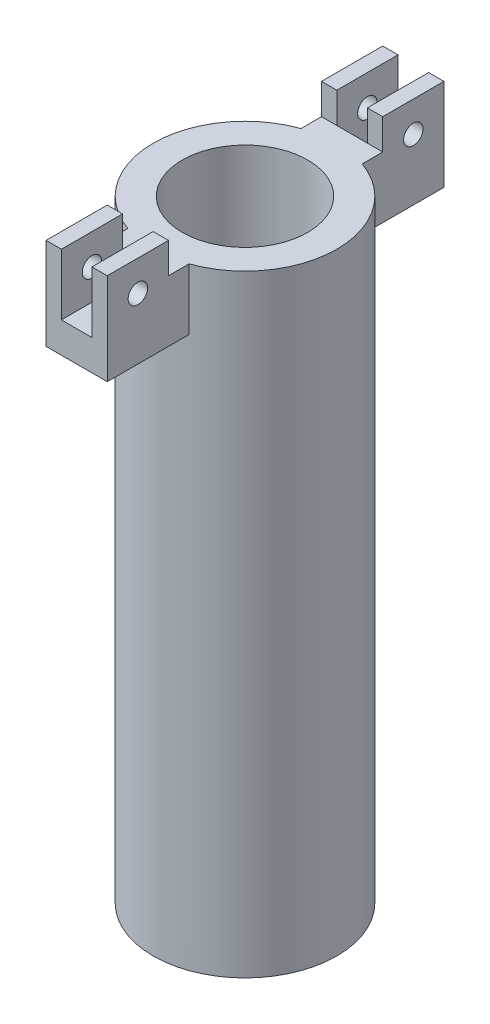
SolidWorks part; units mm, degrees
ref_plane "Front Plane" through (0, 0, 0) normal (0, 0, 1) x (1, 0, 0)
ref_plane "Top Plane" through (0, 0, 0) normal (0, 1, 0) x (1, 0, 0)
ref_plane "Right Plane" through (0, 0, 0) normal (1, 0, 0) x (0, 0, -1)
sketch "Sketch1" plane through (0, 0, 0) normal (0, 1, 0) x (1, 0, 0)
  circle A0 centre (0, 0) radius 30
  dimension "D1" = 60
extrude "Boss-Extrude1" add sketch "Sketch1" along normal mid plane 200
sketch "Sketch2" plane through (0, 100, 0) normal (0, 1, 0) x (1, 0, 0)
  circle A0 centre (0, 0) radius 20.5
  dimension "D1" = 41
extrude "Cut-Extrude1" cut sketch "Sketch2" against normal blind 150
sketch "Sketch3" plane through (0, 0, 0) normal (1, 0, 0) x (0, 0, -1)
  line L0 (20.5, 104.0939) -> (20.5, -49895.9061) construction
  line L1 (20.5, 100) -> (35, 100)
  line L2 (35, 100) -> (35, 110)
  line L3 (35, 110) -> (55, 110)
  line L4 (55, 110) -> (55, 80)
  line L5 (55, 80) -> (20.5, 80)
  line L6 (20.5, 100) -> (20.5, 80)
  line L8 (0, -1000) -> (0, 49000) construction
  line L9 (30, 100) -> (-30, 100) construction
  circle A0 centre (45, 100) radius 3.175
  dimension "D4" = 6.35
  dimension "D1" = 20
  dimension "D3" = 20
  dimension "D5" = 10
  dimension "D6" = 10
  dimension "D8" = 45
extrude "Boss-Extrude3" add sketch "Sketch3" along normal mid plane 20
sketch "Sketch4" plane through (0, 0, -55) normal (0, 0, -1) x (-1, 0, 0)
  line L0 (-10, 110) -> (10, 110) construction
  line L1 (-5, 110) -> (5, 110)
  line L2 (-5, 110) -> (-5, 90)
  line L3 (-5, 90) -> (5, 90)
  line L4 (5, 110) -> (5, 90)
  line L5 (0, 110) -> (0, 80) construction
  line L6 (-10, 80) -> (10, 80) construction
  point P10 (0, 0)
  dimension "D1" = 10
  dimension "D2" = 20
extrude "Cut-Extrude2" cut sketch "Sketch4" against normal up to surface (20 mm away) up to face at (0, 105, -35)
mirror "Mirror1" about plane through (0, 0, 0) normal (0, 0, 1) of "Cut-Extrude2", "Boss-Extrude3"
